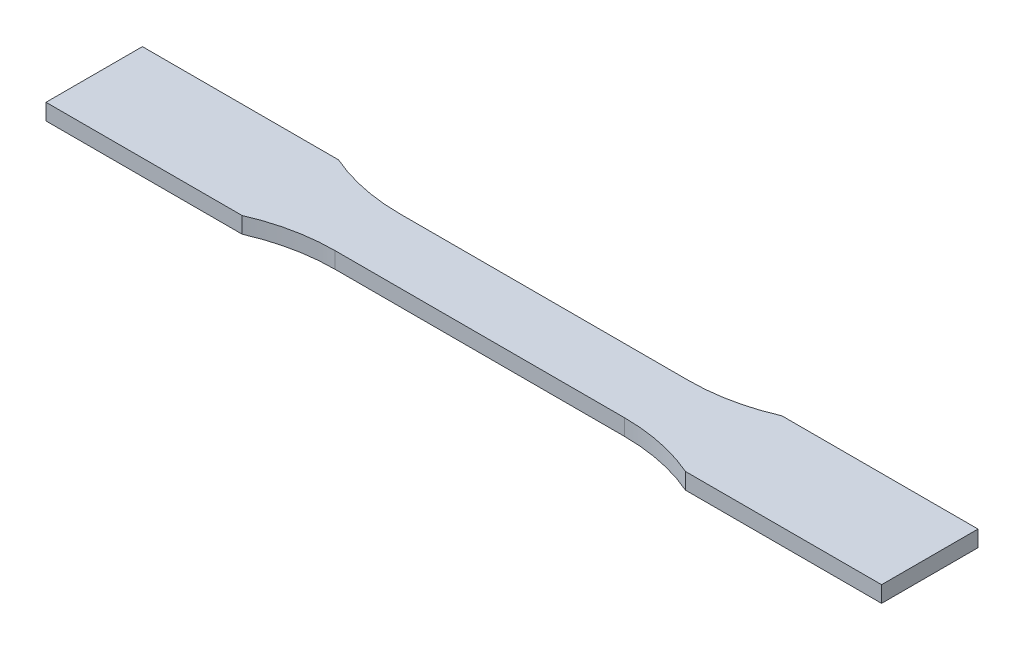
SolidWorks part; units mm, degrees
ref_plane "Front Plane" through (0, 0, 0) normal (0, 0, 1) x (1, 0, 0)
ref_plane "Top Plane" through (0, 0, 0) normal (0, 1, 0) x (1, 0, 0)
ref_plane "Right Plane" through (0, 0, 0) normal (1, 0, 0) x (0, 0, -1)
sketch "Sketch1" plane through (0, 0, 0) normal (0, 1, 0) x (1, 0, 0)
  line L0 (-28.575, -6.35) -> (0, 0) construction
  line L1 (-28.575, 6.35) -> (28.575, 6.35)
  line L2 (-28.575, 6.35) -> (-28.575, -6.35)
  line L3 (-28.575, -6.35) -> (28.575, -6.35)
  line L4 (28.575, 6.35) -> (28.575, -6.35)
  line L5 (0, 0) -> (28.575, 6.35) construction
  line L7 (-82.55, 9.525) -> (82.55, 9.525)
  line L8 (-82.55, 9.525) -> (-82.55, -9.525)
  line L9 (-82.55, -9.525) -> (82.55, -9.525)
  line L10 (82.55, 9.525) -> (82.55, -9.525)
  line L11 (-82.55, 9.525) -> (82.55, -9.525) construction
  circle A0 centre (-28.575, -44.45) radius 38.1
  circle A1 centre (28.575, -44.45) radius 38.1
  circle A2 centre (28.575, 44.45) radius 38.1
  circle A3 centre (-28.575, 44.45) radius 38.1
  dimension "D5" = 76.2
  dimension "D6" = 76.2
  dimension "D7" = 76.2
  dimension "D8" = 76.2
  dimension "D1" = 57.15
  dimension "D2" = 12.7
  dimension "D3" = 165.1
  dimension "D4" = 19.05
extrude "Boss-Extrude1" add sketch "Sketch1" along normal blind 3.2 contours A3 L7 L8 L9 A0 L2 | L4 L1 L2 L3 | A2 L4 A1 L9 L10 L7
sketch "Sketch2" plane through (0, 3.2, 0) normal (0, 1, 0) x (1, 0, 0)
  line L0 (-28.575, 6.35) -> (28.575, 6.35) construction
  line L1 (-28.575, 6.35) -> (28.575, 6.35)
  line L2 (-28.575, 6.35) -> (-28.575, -6.35)
  line L3 (-28.575, -6.35) -> (28.575, -6.35)
  line L4 (28.575, 6.35) -> (28.575, -6.35)
  line L6 (-28.575, 6.35) -> (28.575, 6.35)
  line L7 (-28.575, 6.35) -> (-28.575, 5.08)
  line L8 (-28.575, 5.08) -> (28.575, 5.08)
  line L9 (28.575, 6.35) -> (28.575, 5.08)
  line L10 (-28.575, -6.35) -> (28.575, -6.35)
  line L11 (-28.575, -6.35) -> (-28.575, -4.4582)
  line L12 (-28.575, -4.4582) -> (28.575, -4.4582)
  line L13 (28.575, -6.35) -> (28.575, -4.4582)
  arc A0 (-43.8018, 9.525) -> (-28.575, 6.35) centre (-28.575, 44.45) ccw construction
  dimension "D2" = 12.7
  dimension "D1" = 1.27
equation "\"D6@Sketch1\"=\"D5@Sketch1\""
equation "\"D7@Sketch1\"=\"D5@Sketch1\""
equation "\"D8@Sketch1\"=\"D5@Sketch1\""
equation "\"D1@Sketch2\"=\"D2@Sketch2\"/10"
